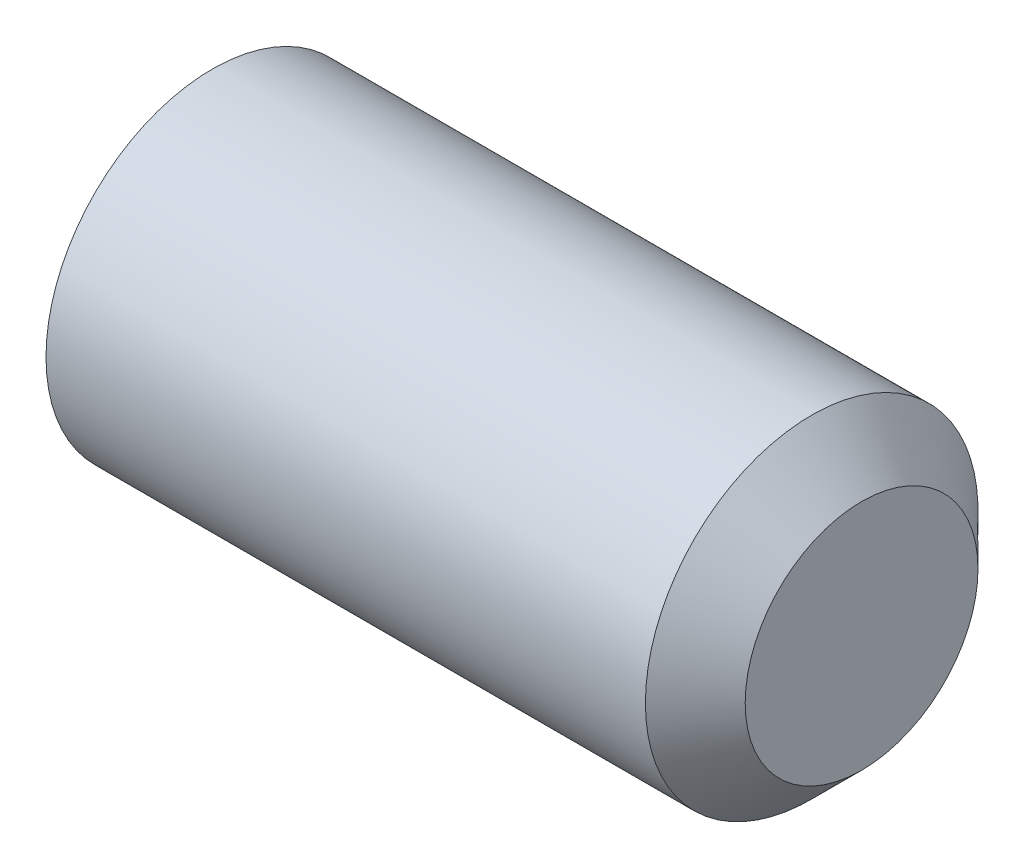
SolidWorks part; units mm, degrees
revolve "BaseBody" add sketch "BodySke" angle 360 about L5
sketch "BodySke" plane through (0, 0, 0) normal (0, 0, 1) x (1, 0, 0)
  line L0 (0, 0) -> (0, 4.172)
  line L1 (0, 4.172) -> (0.478, 5)
  line L2 (0.478, 5) -> (18.5, 5)
  line L3 (18.5, 5) -> (20, 3.5)
  line L4 (20, 0) -> (0, 0)
  line L5 (-12.7, 0) -> (88.9, 0) construction
  line L6 (20, 3.5) -> (20, 0)
  line L7 (20, 3.5) -> (20, 13.025) construction
  line L8 (0, -4.172) -> (0.478, -5) construction
  line L9 (1.5, 15.875) -> (1.5, -3.175) construction
  line L10 (18.5, -5) -> (20, -3.5) construction
  dimension "Diameter" = 10
  dimension "Drive_ch_ang" = 60
  dimension "Minor_dia" = 8.344
  dimension "Cup_nose_ang" = 45
  dimension "Cup_dia" = 7
  dimension "Length" = 20
  dimension "Advance" = 1.5
cosmetic thread "ThreadCosmetic" parameters "Thread_minor"=8.344
ref_plane "Plane1" through (0, 0, 0) normal (0, 0, 1) x (1, 0, 0)
ref_plane "Plane2" through (0, 0, 0) normal (0, 1, 0) x (1, 0, 0)
ref_plane "Plane3" through (0, 0, 0) normal (1, 0, 0) x (0, 0, -1)
other "Configuration Table"
sketch "Sketch2" plane through (0, 0, 0) normal (-1, 0, 0) x (0, 0, 1)
  line L0 (1.4434, 2.5) -> (-1.4434, 2.5)
  line L1 (-1.4434, 2.5) -> (-2.8868, 0)
  line L2 (1.4434, 2.5) -> (2.8868, 0)
  line L3 (1.4434, -2.5) -> (2.8868, 0)
  line L4 (1.4434, -2.5) -> (-1.4434, -2.5)
  line L5 (-1.4434, -2.5) -> (-2.8868, 0)
  dimension "Hex_size" = 5
  dimension "D2" = 2.5
  dimension "D3" = 2.5
extrude "Hex" cut sketch "Sketch2" against normal blind 5
sketch "Sketch4" plane through (0, 4.7709, -0.5249) normal (-1, 0, 0) x (0, 0, 1)
  line L0 (0.5249, -4.7709) -> (3.3314, -4.7709)
  line L1 (0.5249, -4.7709) -> (6.6732, -1.2211) construction
  line L2 (0.5249, -4.7709) -> (1.9281, -2.3404)
  line L3 (2.8584, -4.1568) -> (3.2099, -3.9539)
  line L4 (2.2234, -3.057) -> (2.5749, -2.8541)
  arc A0 (2.8584, -4.1568) -> (2.2234, -3.057) centre (0.5249, -4.7709) ccw
  arc A1 (3.3314, -4.7709) -> (3.2099, -3.9539) centre (0.5249, -4.7709) ccw
  arc A2 (1.9281, -2.3404) -> (2.5749, -2.8541) centre (0.5249, -4.7709) cw
  circle A3 centre (0.5249, -4.7709) radius 2.413 construction
  circle A4 centre (0.5249, -4.7709) radius 2.8065 construction
  dimension "Spline_n_dim" = 4.826
  dimension "Spline_m_dim" = 5.613
  dimension "D1" = 30
  dimension "Spline_a_dim" = 60
  dimension "Spline_p_dim" = 1.27
  dimension "D3" = 0.635
extrude "Spline6" [suppressed] cut sketch "Sketch4" against normal blind 5
pattern_circular "CirPattern1" [suppressed] count 6 every 60 about axis through (-12.7, 0, 0) along (1, 0, 0)
sketch "Sketch5" plane through (0, 0.6556, 6.6316) normal (-1, 0, 0) x (0, 0, 1)
  line L0 (-6.6316, -0.6556) -> (-3.8251, -0.6556)
  line L1 (-6.6316, -0.6556) -> (-1.6115, 4.3645) construction
  line L2 (-6.6316, -0.6556) -> (-6.6316, 2.1509)
  line L3 (-4.4764, 0.6017) -> (-4.2496, 0.8284)
  line L4 (-5.3744, 1.4997) -> (-5.1476, 1.7265)
  line L5 (-5.3744, 1.4997) -> (-4.4764, 0.6017)
  arc A1 (-3.8251, -0.6556) -> (-4.2496, 0.8284) centre (-6.6316, -0.6556) ccw
  arc A2 (-6.6316, 2.1509) -> (-5.1476, 1.7265) centre (-6.6316, -0.6556) cw
  circle A3 centre (-6.6316, -0.6556) radius 2.413 construction
  circle A4 centre (-6.6316, -0.6556) radius 2.8065 construction
  dimension "Spline_n_dim" = 4.826
  dimension "Spline_m_dim" = 5.613
  dimension "Spline_p_dim" = 1.27
  dimension "D3" = 0.635
  dimension "D1" = 45
  dimension "Spline_a_dim" = 90
extrude "Spline4" [suppressed] cut sketch "Sketch5" against normal blind 5
pattern_circular "CirPattern2" [suppressed] count 4 every 90 about axis through (-12.7, 0, 0) along (1, 0, 0)
sketch "ThdSchSke" plane through (0, 0, 0) normal (0, 0, 1) x (1, 0, 0)
  line L0 (0.478, -4.172) -> (-0.1017, -5)
  line L1 (0.478, -4.172) -> (1.0578, -5)
  line L2 (1.0578, -5) -> (1.0578, -6.25)
  line L3 (-3.175, 0) -> (5.1513, 0) construction
  line L4 (0.478, 5) -> (0.478, -5) construction
  line L5 (1.0578, -6.25) -> (-0.1017, -6.25)
  line L6 (-0.1017, -6.25) -> (-0.1017, -5)
  dimension "Thread_minor" = 8.344
  dimension "Diameter" = 10
revolve "ThreadSchematic" [suppressed] cut sketch "ThdSchSke" angle 360 about L3
pattern_linear "ThdSchPat" [suppressed]
equation "\"D2@Sketch2\" = \"Hex_size@Sketch2\" / 2"
equation "\"D3@Sketch2\" = \"Hex_size@Sketch2\" / 2"
equation "\"Thread_minor@ThreadCosmetic\" = \"Minor_dia@BodySke\""
equation "\"D1@Sketch4\" = \"Spline_a_dim@Sketch4\" / 2"
equation "\"D3@Sketch4\" = \"Spline_p_dim@Sketch4\" / 2"
equation "\"D2@CirPattern1\" = \"Spline_a_dim@Sketch4\""
equation "\"Num_teeth@CirPattern1\" = 360 / \"D2@CirPattern1\""
equation "\"Spline_a_dim@Sketch5\" = 90"
equation "\"Spline_p_dim@Sketch5\" = \"Spline_p_dim@Sketch4\""
equation "\"Spline_m_dim@Sketch5\" = \"Spline_m_dim@Sketch4\""
equation "\"Spline_n_dim@Sketch5\" = \"Spline_n_dim@Sketch4\""
equation "\"D1@Sketch5\" = \"Spline_a_dim@Sketch5\" / 2"
equation "\"D3@Sketch5\" = \"Spline_p_dim@Sketch5\" / 2"
equation "\"Key_eng@Spline4\" = \"Key_eng@Spline6\""
equation "\"Thread_minor@ThdSchSke\" = \"Thread_minor@ThreadCosmetic\""
equation "\"Diameter@ThdSchSke\" = \"Diameter@BodySke\""
equation "\"Overcut@ThdSchSke\" = \"Diameter@BodySke\" * 1.25"
equation "\"Num_threads@ThdSchPat\" = int( (\"Length@BodySke\" - ( ( ( \"Diameter@BodySke\" - \"Minor_dia@BodySke\" ) * 0.5 ) / tan( \"Drive_ch_ang@BodySke\" * 0.017453292 ) ) - ( ( ( \"Diameter@BodySke\" - \"Cup_dia@BodySke\" ) * 0.5 ) * tan( \"Cup_nose_ang@BodySke\" * 0.017453292 ) ) ) / \"Advance@BodySke\" + 0.999 )  + 1"
equation "\"Advance@ThdSchPat\" = (\"Length@BodySke\" - ( ( ( \"Diameter@BodySke\" - \"Minor_dia@BodySke\" ) * 0.5 ) / tan( \"Drive_ch_ang@BodySke\" * 0.017453292 ) ) - ( ( ( \"Diameter@BodySke\" - \"Cup_dia@BodySke\" ) * 0.5 ) * tan( \"Cup_nose_ang@BodySke\" * 0.017453292 ) ) ) /  (\"Num_threads@ThdSchPat\" - 1) 'relax it"
equation "' \"Num_threads@ThdSchPat\" = \"Num_threads@ThdSchPat\" - sgn( \"Num_threads@ThdSchPat\" - 1) '---chamfered tips only---"
